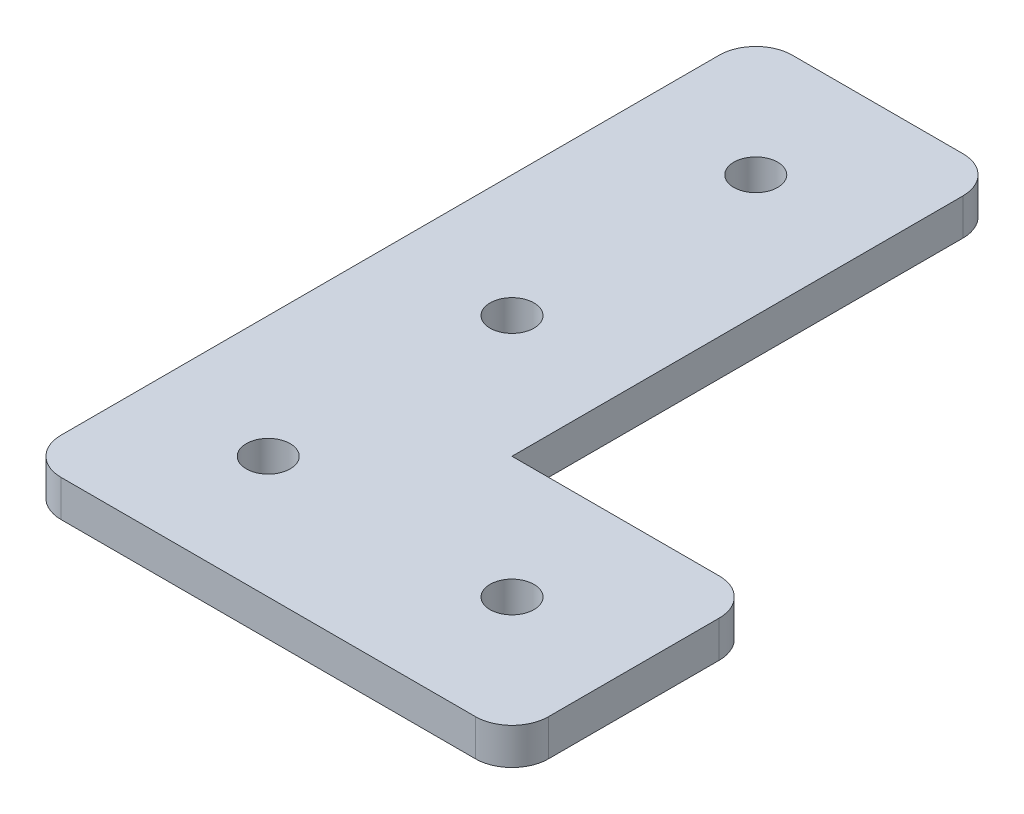
SolidWorks part; units mm, degrees
ref_plane "前视基准面" through (0, 0, 0) normal (0, 0, 1) x (1, 0, 0)
ref_plane "上视基准面" through (0, 0, 0) normal (0, 1, 0) x (1, 0, 0)
ref_plane "右视基准面" through (0, 0, 0) normal (1, 0, 0) x (0, 0, -1)
sketch "草图1" plane through (0, 0, 0) normal (0, 1, 0) x (1, 0, 0)
  line L1 (-20, -10) -> (20, -10)
  line L2 (-20, -10) -> (-20, 10)
  line L3 (-20, 10) -> (20, 10)
  line L4 (20, -10) -> (20, 10)
  line L5 (-20, -10) -> (20, 10) construction
  line L6 (-20, 10) -> (20, -10) construction
  line L7 (0, 10) -> (-20, 10)
  line L8 (0, 10) -> (0, 50)
  line L9 (0, 50) -> (-20, 50)
  line L10 (-20, 10) -> (-20, 50)
  circle A0 centre (-10, 40) radius 1.8
  circle A1 centre (-10, 20) radius 1.8
  circle A2 centre (-10, 0) radius 1.8
  circle A3 centre (10, 0) radius 1.8
  point P0 (0, 0)
  dimension "D5" = 3.6
  dimension "D1" = 20
  dimension "D2" = 20
  dimension "D3" = 40
  dimension "D4" = 40
  dimension "D6" = 10
  dimension "D7" = 20
  dimension "D8" = 10
  dimension "D9" = 10
  dimension "D10" = 10
  dimension "D11" = 10
  dimension "D12" = 10
extrude "凸台-拉伸1" add sketch "草图1" along normal blind 3 contours L10 L3 L8 L9 A1 A0 | L1 L4 L3 L2 A3 A2
fillet "圆角1" radius 3 5 edges at (-20, 1.5, -50) (0, 1.5, -50) (20, 1.5, -10) (20, 1.5, 10) (-20, 1.5, 10)
